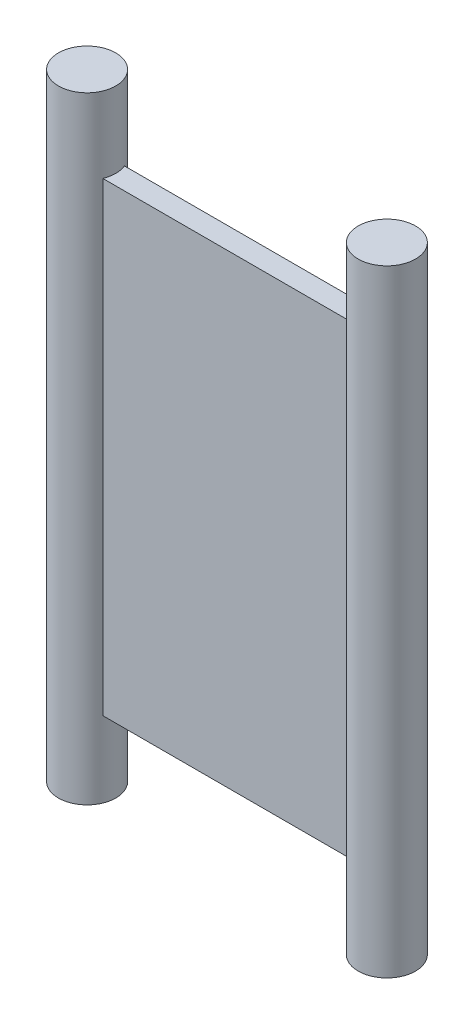
SolidWorks part; units mm, degrees
ref_plane "Front Plane" through (0, 0, 0) normal (0, 0, 1) x (1, 0, 0)
ref_plane "Top Plane" through (0, 0, 0) normal (0, 1, 0) x (1, 0, 0)
ref_plane "Right Plane" through (0, 0, 0) normal (1, 0, 0) x (0, 0, -1)
sketch "Sketch1" plane through (0, 0, 0) normal (0, 1, 0) x (1, 0, 0)
  line L1 (6.9265, 0.5) -> (-6.9265, 0.5)
  line L2 (6.9265, 0.5) -> (6.9265, -0.5)
  line L3 (6.9265, -0.5) -> (-6.9265, -0.5)
  line L4 (-6.9265, 0.5) -> (-6.9265, -0.5)
  line L5 (6.9265, 0.5) -> (-6.9265, -0.5) construction
  line L6 (6.9265, -0.5) -> (-6.9265, 0.5) construction
  point P0 (0, 0)
  dimension "D1" = 13.853
  dimension "D3" = 1
extrude "Boss-Extrude1" add sketch "Sketch1" along normal blind 21.5
ref_plane "Plane1" through (0, 10.75, 0) normal (0, 1, 0) x (1, 0, 0)
sketch "Sketch2" plane through (0, 10.75, 0) normal (0, 1, 0) x (1, 0, 0)
  line L0 (6.9265, -0.5) -> (6.9265, 0.5) construction
  line L1 (-6.9265, 0.5) -> (-6.9265, -0.5) construction
  line L2 (6.9265, -0.5) -> (6.9265, 0.5) construction
  line L3 (-6.9265, 0.5) -> (-6.9265, -0.5) construction
  circle A0 centre (-6.9265, 0) radius 1.325
  circle A1 centre (6.9265, 0) radius 1.325
  dimension "D1" = 2.65
extrude "Boss-Extrude2" add sketch "Sketch2" along normal mid plane 28.5
